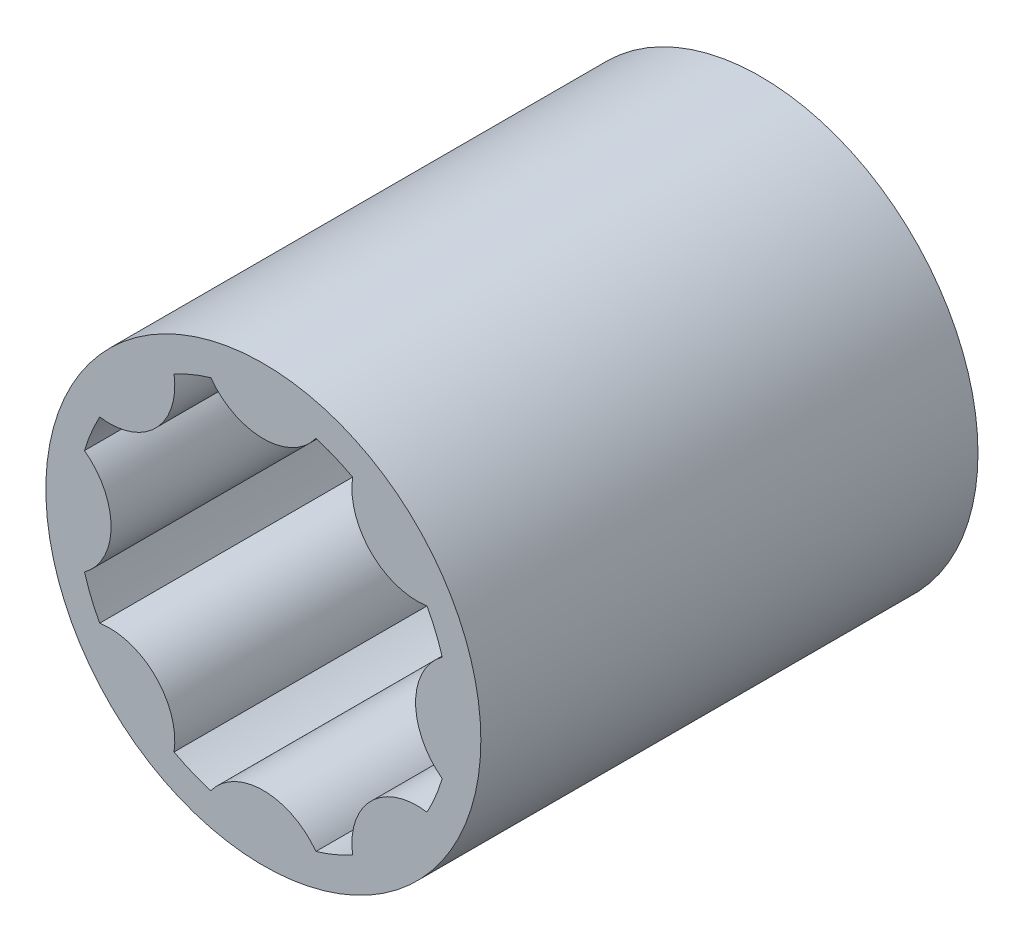
SolidWorks part; units mm, degrees
ref_plane "Ön Düzlem" through (0, 0, 0) normal (0, 0, 1) x (1, 0, 0)
ref_plane "Üst Düzlem" through (0, 0, 0) normal (0, 1, 0) x (1, 0, 0)
ref_plane "Sağ Düzlem" through (0, 0, 0) normal (1, 0, 0) x (0, 0, -1)
sketch "Sketch1" plane through (0, 0, 0) normal (0, 0, 1) x (1, 0, 0)
  arc A0 (-13.1674, 7.1846) -> (-14.3911, 4.2305) centre (0, 0) ccw
  arc A1 (-4.2305, 14.3911) -> (-7.1846, 13.1674) centre (0, 0) ccw
  circle A2 centre (0, 0) radius 17.5
  arc A3 (-4.2305, 14.3911) -> (4.2305, 14.3911) centre (0, 17.5) ccw
  arc A4 (7.1846, 13.1674) -> (13.1674, 7.1846) centre (12.3744, 12.3744) ccw
  arc A5 (14.3911, 4.2305) -> (14.3911, -4.2305) centre (17.5, 0) ccw
  arc A6 (13.1674, -7.1846) -> (7.1846, -13.1674) centre (12.3744, -12.3744) ccw
  arc A7 (4.2305, -14.3911) -> (-4.2305, -14.3911) centre (0, -17.5) ccw
  arc A8 (-7.1846, -13.1674) -> (-13.1674, -7.1846) centre (-12.3744, -12.3744) ccw
  arc A9 (-14.3911, -4.2305) -> (-14.3911, 4.2305) centre (-17.5, 0) ccw
  arc A10 (-13.1674, 7.1846) -> (-7.1846, 13.1674) centre (-12.3744, 12.3744) ccw
  arc A11 (-14.3911, -4.2305) -> (-13.1674, -7.1846) centre (0, 0) ccw
  arc A12 (-7.1846, -13.1674) -> (-4.2305, -14.3911) centre (0, 0) ccw
  arc A13 (4.2305, -14.3911) -> (7.1846, -13.1674) centre (0, 0) ccw
  arc A14 (13.1674, -7.1846) -> (14.3911, -4.2305) centre (0, 0) ccw
  arc A15 (14.3911, 4.2305) -> (13.1674, 7.1846) centre (0, 0) ccw
  arc A16 (7.1846, 13.1674) -> (4.2305, 14.3911) centre (0, 0) ccw
  dimension "D1" = 8
extrude "Boss-Extrude1" add sketch "Sketch1" along normal blind 40
